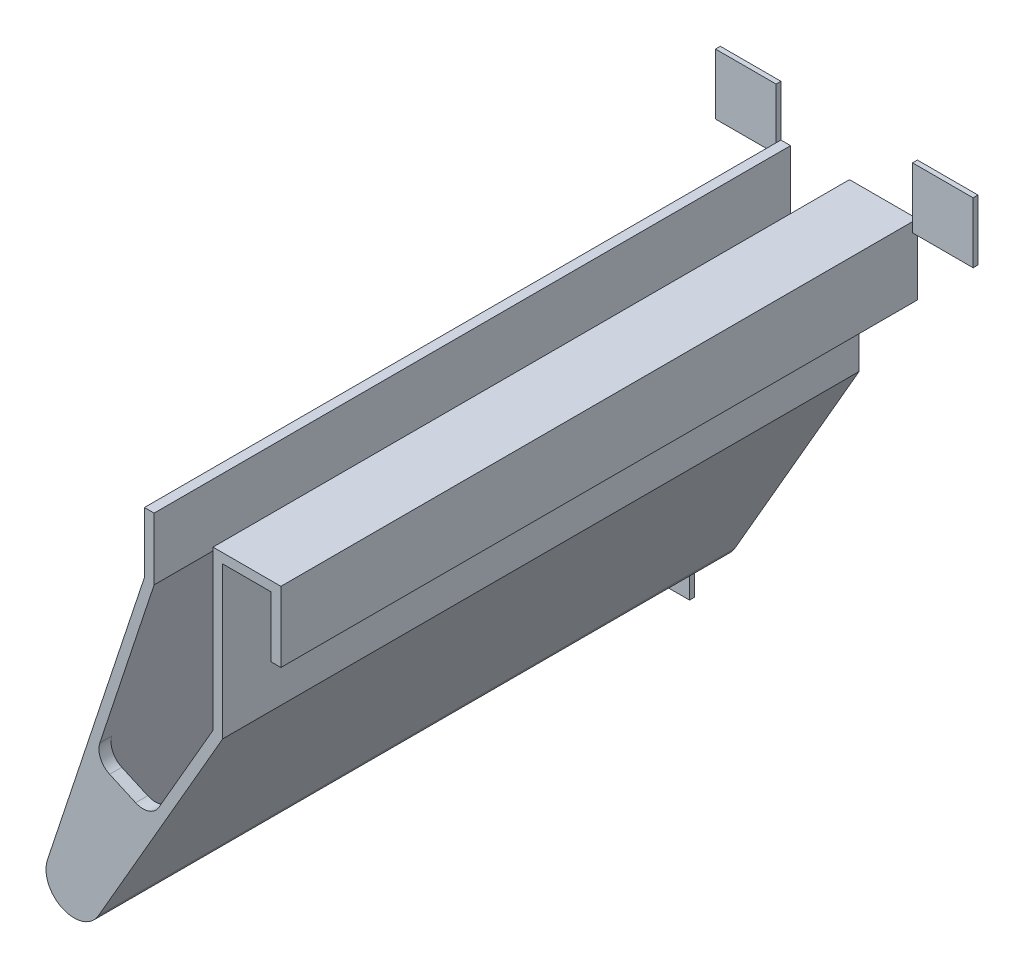
SolidWorks part; units mm, degrees
ref_plane "Front Plane" through (0, 0, 0) normal (0, 0, 1) x (1, 0, 0)
ref_plane "Top Plane" through (0, 0, 0) normal (0, 1, 0) x (1, 0, 0)
ref_plane "Right Plane" through (0, 0, 0) normal (1, 0, 0) x (0, 0, -1)
sketch "Sketch1" plane through (0, 0, 0) normal (0, 0, 1) x (1, 0, 0)
  line L0 (0, 0) -> (0, 10)
  line L1 (0, 10) -> (-8, 10)
  line L2 (-8, 10) -> (-8, -15)
  line L3 (-8, -15) -> (-28.5122, -50.5282)
  line L4 (0, 0) -> (1.6, 0)
  line L5 (1.6, 0) -> (1.6, 11.6)
  line L6 (1.6, 11.6) -> (-9.6, 11.6)
  line L7 (-9.6, 11.6) -> (-9.6, -14.5713)
  line L8 (0, 10) -> (0, 11.6) construction
  line L9 (-8, 10) -> (-9.6, 10) construction
  line L10 (-9.6, 11.6) -> (-29.8978, -49.7282) construction
  line L11 (-29.8978, -49.7282) -> (-35.594, -47.8429) construction
  line L12 (-35.594, -47.8429) -> (-15.2961, 13.4853) construction
  line L13 (-15.2961, 13.4853) -> (-9.6, 11.6) construction
  line L14 (-9.6, -14.5713) -> (-29.8978, -49.7282)
  line L15 (-9.6, -14.5713) -> (-8.2144, -15.3713) construction
  line L18 (-20.9152, 1.6) -> (-36.92, -46.7572)
  line L19 (-35.401, -47.2599) -> (-19.3152, 1.3421)
  line L20 (-19.3152, 1.3421) -> (-19.3152, 11.6)
  line L21 (-19.3152, 11.6) -> (-20.9152, 11.6)
  line L22 (-20.9152, 11.6) -> (-20.9152, 1.6)
  line L23 (-20.9152, 1.6) -> (-19.3962, 1.0973) construction
  arc A0 (-29.8978, -49.7282) -> (-35.401, -47.2599) centre (-32.5231, -48.2124) cw
  arc A1 (-28.5122, -50.5282) -> (-36.92, -46.7572) centre (-32.5231, -48.2124) cw
  point P18 (-15.9201, 11.6)
  point P19 (0, 0)
  point P26 (0, 0)
  dimension "D1" = 10
  dimension "D2" = 8
  dimension "D3" = 1.6
  dimension "D4" = 25
  dimension "D5" = 30
  dimension "D6" = 62
  dimension "D7" = 6
  dimension "D8" = 10
extrude "Boss-Extrude1" add sketch "Sketch1" along normal blind 105
ref_plane "Plane1" through (0, 0, 52.5) normal (0, 0, 1) x (1, 0, 0)
sketch "Sketch2" plane through (0, 0, 0) normal (0, 0, -1) x (-1, 0, 0)
  line L0 (35.401, -47.2599) -> (29.1168, -28.2729)
  line L1 (35.401, -47.2599) -> (19.3152, 1.3421) construction
  line L2 (29.1168, -28.2729) -> (19.8978, -32.4076)
  line L3 (9.6, -14.5713) -> (29.8978, -49.7282) construction
  line L4 (19.8978, -32.4076) -> (29.8978, -49.7282)
  arc A0 (29.8978, -49.7282) -> (35.401, -47.2599) centre (32.5231, -48.2124) ccw
  arc A1 (29.8978, -49.7282) -> (35.401, -47.2599) centre (32.5231, -48.2124) ccw construction
  dimension "D1" = 20
extrude "Boss-Extrude2" add sketch "Sketch2" against normal blind 2
mirror "Mirror1" about plane through (0, 0, 52.5) normal (0, 0, 1) of "Boss-Extrude2"
fillet "Fillet1" radius 3 4 edges at (-29.1168, -28.2729, 104) (-19.8978, -32.4076, 104) (-19.8978, -32.4076, 1) (-29.1168, -28.2729, 1)
sketch "Sketch3" plane through (0, 0, 52.5) normal (0, 0, 1) x (1, 0, 0)
  line L0 (-32.5231, -48.2124) -> (-34.0942, -52.9592) construction
  line L1 (-32.1434, -48.3381) -> (-33.7144, -53.0849)
  line L2 (-32.9029, -48.0868) -> (-34.4739, -52.8335)
  line L3 (-29.8978, -49.7282) -> (-35.594, -47.8429) construction
  arc A0 (-32.1434, -48.3381) -> (-32.9029, -48.0868) centre (-32.5231, -48.2124) ccw
  arc A1 (-34.4739, -52.8335) -> (-33.7144, -53.0849) centre (-34.0942, -52.9592) ccw
  point P3 (-33.3086, -50.5858)
  dimension "D1" = 0.8
  dimension "D2" = 5
extrude "Cut-Extrude1" cut sketch "Sketch3" against normal blind 40 and the other way blind 40
sketch "Sketch4" plane through (0, 0, 0) normal (0, 0, -1) x (-1, 0, 0)
  line L0 (-1.6, 0) -> (-1.6, 11.6) construction
  line L1 (-11.6, 20) -> (-1.6, 20)
  line L2 (-11.6, 20) -> (-11.6, 10)
  line L3 (-11.6, 10) -> (-1.6, 10)
  line L4 (-1.6, 20) -> (-1.6, 10)
  line L5 (-6.6, 10) -> (-6.6, 20) construction
  line L6 (-11.6, 15) -> (-1.6, 15) construction
  line L7 (30.9152, 20) -> (20.9152, 20)
  line L8 (30.9152, 20) -> (30.9152, 10)
  line L9 (30.9152, 10) -> (20.9152, 10)
  line L10 (20.9152, 20) -> (20.9152, 10)
  line L11 (25.9152, 10) -> (25.9152, 20) construction
  line L12 (30.9152, 15) -> (20.9152, 15) construction
  line L13 (35.1831, -50.8724) -> (45.1831, -50.8724)
  line L14 (35.1831, -50.8724) -> (35.1831, -60.8724)
  line L15 (35.1831, -60.8724) -> (45.1831, -60.8724)
  line L16 (45.1831, -50.8724) -> (45.1831, -60.8724)
  line L17 (40.1831, -60.8724) -> (40.1831, -50.8724) construction
  line L18 (35.1831, -55.8724) -> (45.1831, -55.8724) construction
  line L19 (-1.6, 11.6) -> (9.6, 11.6) construction
  line L20 (20.9152, 11.6) -> (20.9152, 1.6) construction
  line L21 (19.3152, 11.6) -> (20.9152, 11.6) construction
  line L22 (35.1831, -50.8724) -> (35.798, -51.4874) construction
  line L23 (35.1831, -52.0038) -> (36.3145, -50.8724) construction
  arc A0 (28.5122, -50.5282) -> (36.92, -46.7572) centre (32.5231, -48.2124) ccw construction
  point P22 (0, 0)
  point P27 (0, 0)
  point P28 (33.8093, -51.9585)
  point P29 (35.7488, -51.4381)
  point P188 (-6.6, 15)
  point P249 (25.9152, 15)
  point P542 (40.1831, -55.8724)
  dimension "D1" = 10
  dimension "D2" = 1.6
  dimension "D3" = 1.6
  dimension "D4" = 1.6
extrude "Boss-Extrude3" add sketch "Sketch4" against normal blind 0.8
